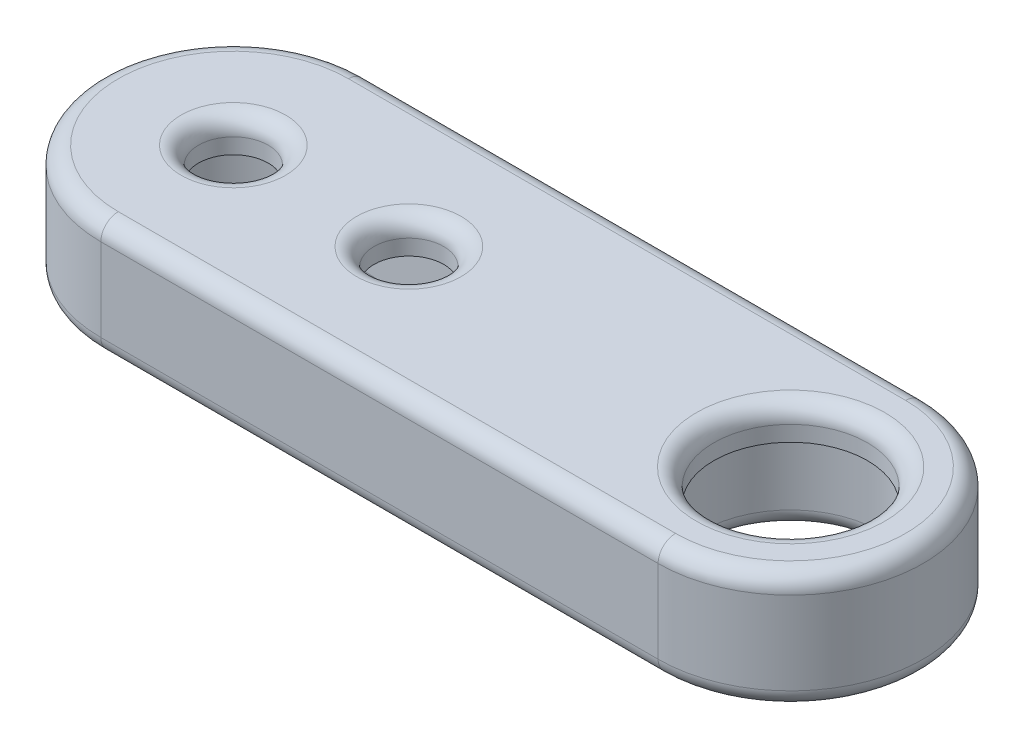
SolidWorks part; units mm, degrees
ref_plane "Front Plane" through (0, 0, 0) normal (0, 0, 1) x (1, 0, 0)
ref_plane "Top Plane" through (0, 0, 0) normal (0, 1, 0) x (1, 0, 0)
ref_plane "Right Plane" through (0, 0, 0) normal (1, 0, 0) x (0, 0, -1)
sketch "Sketch1" plane through (0, 0, 0) normal (0, 1, 0) x (1, 0, 0)
  line L0 (2.2864, 2.65) -> (14.1103, 1.997)
  line L1 (2.2864, -2.65) -> (14.1103, -1.997)
  line L2 (0, 0) -> (14, 0) construction
  line L4 (0, 6.04) -> (25.4, 6.04)
  line L8 (0, -6.04) -> (25.4, -6.04)
  circle A0 centre (0, 0) radius 3.5 construction
  arc A1 (14.1103, 1.997) -> (14.1103, -1.997) centre (14, 0) cw
  arc A2 (2.2864, 2.65) -> (2.2864, -2.65) centre (0, 0) ccw
  circle A3 centre (14, 0) radius 0.5 construction
  circle A4 centre (12, 0) radius 0.5 construction
  circle A5 centre (10, 0) radius 0.5 construction
  circle A6 centre (8, 0) radius 0.5 construction
  circle A7 centre (6, 0) radius 0.5 construction
  circle A8 centre (4, 0) radius 0.5 construction
  arc A12 (0, -6.04) -> (0, 6.04) centre (0, 0) cw
  circle A17 centre (25.4, 0) radius 4.064
  arc A18 (25.4, -6.04) -> (25.4, 6.04) centre (25.4, 0) ccw
  point P4 (16, 0)
  point P6 (-3.5, 0)
  point P12 (24.1547, -6.04)
  point P22 (0, 0)
  dimension "D1" = 7
  dimension "D5" = 1
  dimension "D8" = 2.54
  dimension "D10" = 25.4
  dimension "D4" = 2
  dimension "D9" = 8.128
  dimension "D2" = 19.5
  dimension "D3" = 5.3
  dimension "D7" = 2
  dimension "D6" = 6
extrude "Boss-Extrude1" add sketch "Sketch1" along normal blind 4.5
sketch "Sketch2" plane through (0, 4.5, 0) normal (0, 1, 0) x (1, 0, 0)
  line L0 (0, 0) -> (16, 0) construction
  line L4 (25.4, 6.04) -> (0, 6.04)
  line L5 (0, -6.04) -> (25.4, -6.04)
  line L8 (25.4, 6.04) -> (0, 6.04)
  line L9 (0, -6.04) -> (25.4, -6.04)
  circle A0 centre (0, 0) radius 1.5875
  circle A1 centre (8, 0) radius 1.5875
  arc A2 (14.1103, -1.997) -> (14.1103, 1.997) centre (14, 0) ccw construction
  circle A3 centre (25.4, 0) radius 3.5
  arc A5 (25.4, -6.04) -> (25.4, 6.04) centre (25.4, 0) ccw
  arc A6 (25.4, -6.04) -> (25.4, 6.04) centre (25.4, 0) ccw
  arc A9 (0, 6.04) -> (0, -6.04) centre (0, 0) ccw
  arc A17 (0, 6.04) -> (0, -6.04) centre (0, 0) ccw
  point P15 (8, 0)
  dimension "D2" = 3.175
  dimension "D3" = 3.175
  dimension "D4" = 7
  dimension "D1" = 0
extrude "Boss-Extrude2" add sketch "Sketch2" along normal offset from surface (1.5 mm away) 6 up to face at (7.2242, 0, 0)
sketch "Sketch3" plane through (0, 0, 0) normal (0, -1, 0) x (1, 0, 0)
  line L6 (25.4, 6.04) -> (0, 6.04)
  line L7 (0, -6.04) -> (25.4, -6.04)
  line L10 (25.4, 6.04) -> (0, 6.04)
  line L11 (0, -6.04) -> (25.4, -6.04)
  arc A2 (25.4, -6.04) -> (25.4, 6.04) centre (25.4, 0) ccw
  arc A3 (25.4, -6.04) -> (25.4, 6.04) centre (25.4, 0) ccw
  arc A11 (0, 6.04) -> (0, -6.04) centre (0, 0) ccw
  arc A17 (0, 6.04) -> (0, -6.04) centre (0, 0) ccw
  dimension "D1" = 0
extrude "Cut-Extrude1" cut sketch "Sketch3" against normal blind 0.635
fillet "Fillet2" radius 0.7937 9 edges at (12.7, 0.635, -6.04) (-6.04, 0.635, 0) (12.7, 0.635, 6.04) (-3.5, 0.635, 0) (8.1983, 0.635, -2.3235) (16, 0.635, 0) (8.1983, 0.635, 2.3235) (31.44, 0.635, 0) (25.4, 0.635, -4.064)
fillet "Fillet3" radius 0.7937 7 edges at (12.7, 6, 6.04) (-6.04, 6, 0) (12.7, 6, -6.04) (0, 6, -1.5875) (8, 6, -1.5875) (31.44, 6, 0) (25.4, 6, -3.5)
